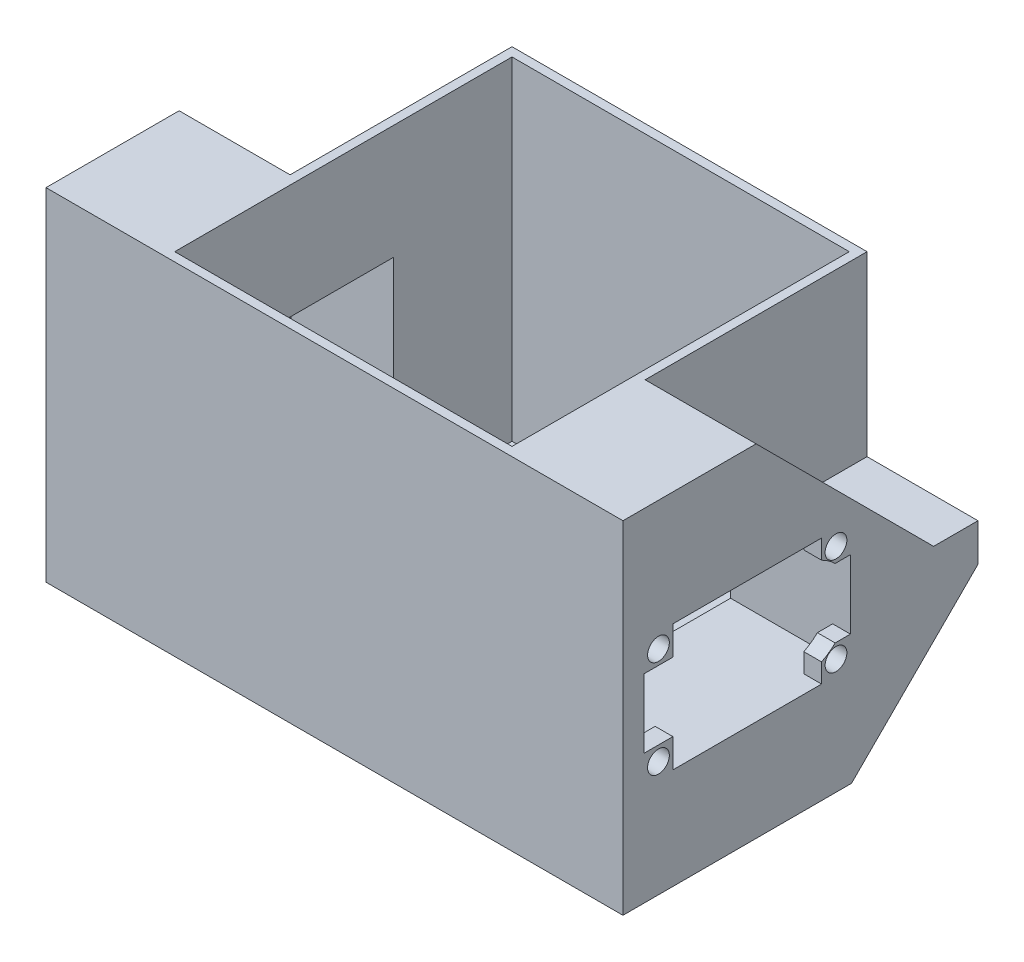
SolidWorks part; units mm, degrees
ref_plane "Front Plane" through (0, 0, 0) normal (0, 0, 1) x (1, 0, 0)
ref_plane "Top Plane" through (0, 0, 0) normal (0, 1, 0) x (1, 0, 0)
ref_plane "Right Plane" through (0, 0, 0) normal (1, 0, 0) x (0, 0, -1)
sketch "Sketch1" plane through (0, 0, 0) normal (0, 1, 0) x (1, 0, 0)
  line L1 (-40, 40) -> (40, 40)
  line L2 (-40, 40) -> (-40, -40)
  line L3 (-40, -40) -> (40, -40)
  line L4 (40, 40) -> (40, -40)
  line L5 (-40, 40) -> (40, -40) construction
  line L6 (-40, -40) -> (40, 40) construction
  circle A0 centre (0, 0) radius 18.4
  point P0 (0, 0)
  dimension "D3" = 36.8
  dimension "D1" = 80
  dimension "D2" = 80
extrude "Boss-Extrude1" add sketch "Sketch1" along normal blind 2
sketch "Sketch2" plane through (0, 2, 0) normal (0, 1, 0) x (1, 0, 0)
  line L1 (40, -40) -> (44, -40)
  line L2 (40, -40) -> (40, -21.5)
  line L3 (40, -21.5) -> (44, -21.5)
  line L4 (44, -40) -> (44, -21.5)
  dimension "D1" = 18.5
  dimension "D2" = 4
extrude "Boss-Extrude2" add sketch "Sketch2" against normal blind 15.25
sketch "Sketch3" plane through (44, 0, 0) normal (1, 0, 0) x (0, 0, -1)
  line L1 (-40, -13.25) -> (-21.5, -13.25) construction
  line L4 (-40, -13.25) -> (-40, 2) construction
  circle A0 centre (-30.75, -8.125) radius 2.2
  dimension "D1" = 4.4
  dimension "D2" = 5.125
  dimension "D3" = 9.25
extrude "Cut-Extrude1" cut sketch "Sketch3" against normal through all
ref_plane "Plane1" through (0, 0, 0) normal (1, 0, 0) x (0, 0, -1)
mirror "Mirror1" about plane through (0, 0, 0) normal (1, 0, 0) of "Cut-Extrude1", "Boss-Extrude2"
ref_plane "Plane2" through (0, 0, 0) normal (0, 0, -1) x (-1, 0, 0)
mirror "Mirror2" about plane through (0, 0, 0) normal (0, 0, -1) of "Mirror1", "Cut-Extrude1", "Boss-Extrude2"
sketch "Sketch4" plane through (0, 2, 0) normal (0, 1, 0) x (1, 0, 0)
  line L1 (44, 40) -> (-44, 40) construction
  line L2 (-40, 21.5) -> (-40, -21.5) construction
  circle A1 centre (-24, 24) radius 2.2
  circle A4 centre (24, 24) radius 2.2
  dimension "D1" = 16
  dimension "D2" = 16
  dimension "D3" = 2
extrude "Cut-Extrude2" cut sketch "Sketch4" against normal through all
mirror "Mirror3" about plane through (0, 0, 0) normal (0, 0, -1) of "Cut-Extrude2"
sketch "Sketch5" plane through (0, 0, 40) normal (0, 0, 1) x (1, 0, 0)
  line L1 (-40, -13.25) -> (-44, -13.25)
  line L2 (-40, -13.25) -> (-40, 2)
  line L3 (-40, 2) -> (-44, 2)
  line L4 (-44, -13.25) -> (-44, 2)
  line L5 (40, -13.25) -> (44, -13.25)
  line L6 (40, -13.25) -> (40, 2)
  line L7 (40, 2) -> (44, 2)
  line L8 (44, -13.25) -> (44, 2)
extrude "Cut-Extrude3" cut sketch "Sketch5" against normal through all
sketch "Sketch6" plane through (0, 2, 0) normal (0, 1, 0) x (1, 0, 0)
  line L1 (-40, 40) -> (40, 40)
  line L2 (-40, 40) -> (-40, -40)
  line L3 (-40, -40) -> (40, -40)
  line L4 (40, 40) -> (40, -40)
  line L5 (38, 38) -> (-38, 38)
  line L6 (38, 38) -> (38, -38)
  line L7 (38, -38) -> (-38, -38)
  line L8 (-38, 38) -> (-38, -38)
  line L9 (38, 38) -> (-38, -38) construction
  line L10 (38, -38) -> (-38, 38) construction
  point P6 (0, 0)
  dimension "D1" = 76
  dimension "D2" = 76
extrude "Boss-Extrude3" add sketch "Sketch6" along normal blind 75
sketch "Sketch7" plane through (0, 0, 40) normal (0, 0, 1) x (1, 0, 0)
  line L0 (40, 0) -> (65, 0)
  line L2 (-40, 0) -> (-65, 0)
  line L4 (-65, 0) -> (-40, 0)
  line L5 (-65, 0) -> (-65, 77)
  line L6 (-65, 77) -> (-40, 77)
  line L7 (-40, 0) -> (-40, 77)
  line L8 (65, 0) -> (40, 0)
  line L9 (65, 0) -> (65, 77)
  line L10 (65, 77) -> (40, 77)
  line L11 (40, 0) -> (40, 77)
  line M4 (40, 0) -> (40, 77)
  line M6 (-40, 77) -> (-40, 0)
  dimension "D1" = 25
  dimension "D2" = 25
extrude "Boss-Extrude4" add sketch "Sketch7" against normal blind 80 contours L6 L5 L2 M6 | L9 L10 L0 M4
sketch "Sketch9" plane through (65, 0, 0) normal (1, 0, 0) x (0, 0, -1)
  line L7 (25.75, 28.5) -> (11.5, 14.25)
  line L8 (40, 0) -> (11.5, 0)
  line L9 (40, 0) -> (40, 28.5)
  line L10 (40, 28.5) -> (11.5, 28.5)
  line L11 (11.5, 0) -> (11.5, 28.5)
  line L12 (11.5, 14.25) -> (11.5, 0)
  line L13 (40, 28.5) -> (11.5, 0)
  line M9 (-40, 0) -> (40, 0)
  line M10 (40, 0) -> (40, 77)
  dimension "D1" = 28.5
  dimension "D2" = 28.5
extrude "Cut-Extrude5" cut sketch "Sketch9" against normal blind 21 contours L13 M10 M9
mirror "Mirror4" about plane through (0, 0, 0) normal (1, 0, 0) of "Cut-Extrude5"
sketch "Sketch11" plane through (0, 0, -40) normal (0, 0, -1) x (-1, 0, 0)
  line L0 (0, 0) -> (0, 46.7557) construction
  line L1 (-65, 77) -> (-40, 77)
  line L2 (-65, 77) -> (-65, 37)
  line L3 (-65, 37) -> (-40, 37)
  line L4 (-40, 77) -> (-40, 37)
  line L5 (-44, 0) -> (44, 0) construction
  line L6 (40, 77) -> (40, 37)
  line L7 (65, 37) -> (40, 37)
  line L8 (65, 77) -> (65, 37)
  line L9 (65, 77) -> (40, 77)
  dimension "D1" = 40
  dimension "D2" = 25
extrude "Cut-Extrude6" cut sketch "Sketch11" against normal blind 50
sketch "Sketch12" plane through (65, 0, 0) normal (1, 0, 0) x (0, 0, -1)
  line L0 (-10, 37) -> (40, 37) construction
  line L5 (-10, 77) -> (30, 77)
  line L6 (-10, 77) -> (-10, 37)
  line L7 (-10, 37) -> (30, 37)
  line L8 (30, 77) -> (30, 37)
  line L9 (-10, 77) -> (30, 37)
  line M3 (40, 37) -> (-10, 37)
  line M4 (-10, 37) -> (-10, 77)
  dimension "D1" = 40
extrude "Boss-Extrude5" add sketch "Sketch12" against normal blind 25 contours L9 M4 M3
mirror "Mirror5" about plane through (0, 0, 0) normal (1, 0, 0) of "Boss-Extrude5"
sketch "Sketch14" plane through (65, 0, 0) normal (1, 0, 0) x (0, 0, -1)
  line L1 (11.25, 22.75) -> (-35.25, 22.75)
  line L2 (11.25, 22.75) -> (11.25, 51.25)
  line L3 (11.25, 51.25) -> (-35.25, 51.25)
  line L4 (-35.25, 22.75) -> (-35.25, 51.25)
  line L6 (-10, 77) -> (-40, 77) construction
  circle A1 centre (0, 37) radius 10.25
  dimension "D1" = 25.75
  dimension "D2" = 11.25
  dimension "D4" = 46.5
  dimension "D5" = 14.25
  dimension "D3" = 28.5
extrude "Cut-Extrude9" cut sketch "Sketch14" against normal blind 34 contours A1 | L4 L1 L2 L3 A1
mirror "Mirror6" about plane through (0, 0, 0) normal (1, 0, 0) of "Cut-Extrude9"
sketch "Sketch15" plane through (65, 0, 0) normal (1, 0, 0) x (0, 0, -1)
  line L0 (-12, 37) -> (-12, 22.75) construction
  line L1 (-35.25, 51.25) -> (11.25, 51.25)
  line L2 (-35.25, 51.25) -> (-35.25, 22.75)
  line L3 (-35.25, 22.75) -> (11.25, 22.75)
  line L4 (11.25, 51.25) -> (11.25, 22.75)
  line L5 (-35.25, 51.25) -> (-28.75, 51.25)
  line L6 (-35.25, 51.25) -> (-35.25, 44.75)
  line L7 (-35.25, 44.75) -> (-28.75, 44.75)
  line L8 (-28.75, 51.25) -> (-28.75, 44.75)
  line L9 (-12, 22.75) -> (-12, 37) construction
  line L10 (-12, 37) -> (-5.1318, 37) construction
  line L11 (-35.25, 29.25) -> (-28.75, 29.25)
  line L12 (-28.75, 22.75) -> (-28.75, 29.25)
  line L13 (4.75, 22.75) -> (4.75, 29.25)
  line L14 (11.25, 29.25) -> (4.75, 29.25)
  line L15 (4.75, 51.25) -> (4.75, 44.75)
  line L16 (11.25, 44.75) -> (4.75, 44.75)
  circle A0 centre (-32, 48) radius 2.45
  circle A1 centre (8, 48) radius 2.45
  circle A2 centre (8, 26) radius 2.45
  circle A3 centre (-32, 26) radius 2.45
  circle A4 centre (0, 37) radius 10.25
  circle A6 centre (0, 37) radius 11
  line M21 (11.25, 22.75) -> (-35.25, 22.75)
  line M22 (-35.25, 22.75) -> (-35.25, 51.25)
  line M23 (-35.25, 51.25) -> (11.25, 51.25)
  line M24 (11.25, 51.25) -> (11.25, 22.75)
  dimension "D1" = 3.25
  dimension "D2" = 3.25
  dimension "D7" = 11.25
  dimension "D5" = 6.5
  dimension "D6" = 6.5
  dimension "D3" = 2
  dimension "D4" = 2
extrude "Boss-Extrude6" add sketch "Sketch15" against normal blind 4 contours L8 L2 L7 A0 M23 | L3 L12 L11 A3 M22 | A6 L13 L4 L14 A2 M21 | A6 L16 L15 A1 M24 M23
mirror "Mirror7" about plane through (0, 0, 0) normal (1, 0, 0) of "Boss-Extrude6"
